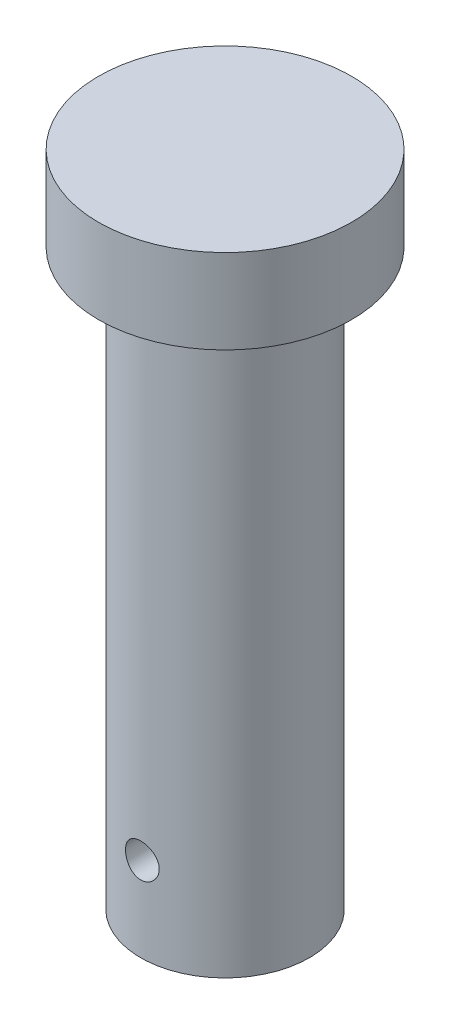
SolidWorks part; units mm, degrees
ref_plane "Front Plane" through (0, 0, 0) normal (0, 0, 1) x (1, 0, 0)
ref_plane "Top Plane" through (0, 0, 0) normal (0, 1, 0) x (1, 0, 0)
ref_plane "Right Plane" through (0, 0, 0) normal (1, 0, 0) x (0, 0, -1)
sketch "Croquis1" plane through (0, 0, 0) normal (0, 1, 0) x (1, 0, 0)
  circle A0 centre (0, 0) radius 22.5
  dimension "D1" = 45
extrude "Saliente-Extruir1" add sketch "Croquis1" against normal blind 15
sketch "Croquis2" plane through (0, -15, 0) normal (0, -1, 0) x (1, 0, 0)
  circle A0 centre (0, 0) radius 15
  dimension "D1" = 30
extrude "Saliente-Extruir2" add sketch "Croquis2" along normal blind 102
sketch "Croquis3" plane through (0, 0, 0) normal (0, 0, 1) x (1, 0, 0)
  line L0 (-15, -117) -> (15, -117) construction
  circle A0 centre (0, -102) radius 3
  dimension "D1" = 6
  dimension "D2" = 15
extrude "Cortar-Extruir1" cut sketch "Croquis3" against normal mid plane 102
